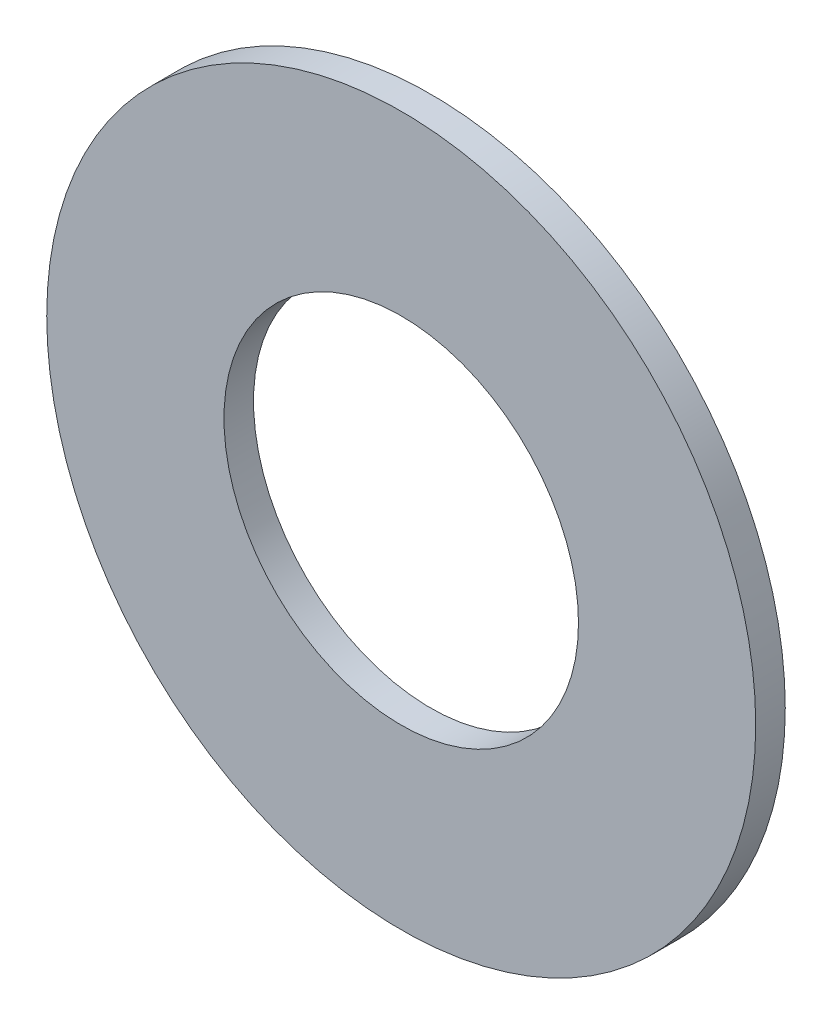
SolidWorks part; units mm, degrees
ref_plane "前视基准面" through (0, 0, 0) normal (0, 0, 1) x (1, 0, 0)
ref_plane "上视基准面" through (0, 0, 0) normal (0, 1, 0) x (1, 0, 0)
ref_plane "右视基准面" through (0, 0, 0) normal (1, 0, 0) x (0, 0, -1)
sketch "草图1" plane through (0, 0, 0) normal (0, 0, 1) x (1, 0, 0)
  circle A0 centre (0, 0) radius 3
  circle A2 centre (0, 0) radius 6
  dimension "D1" = 12
  dimension "D2" = 6
extrude "凸台-拉伸1" add sketch "草图1" along normal blind 0.5
